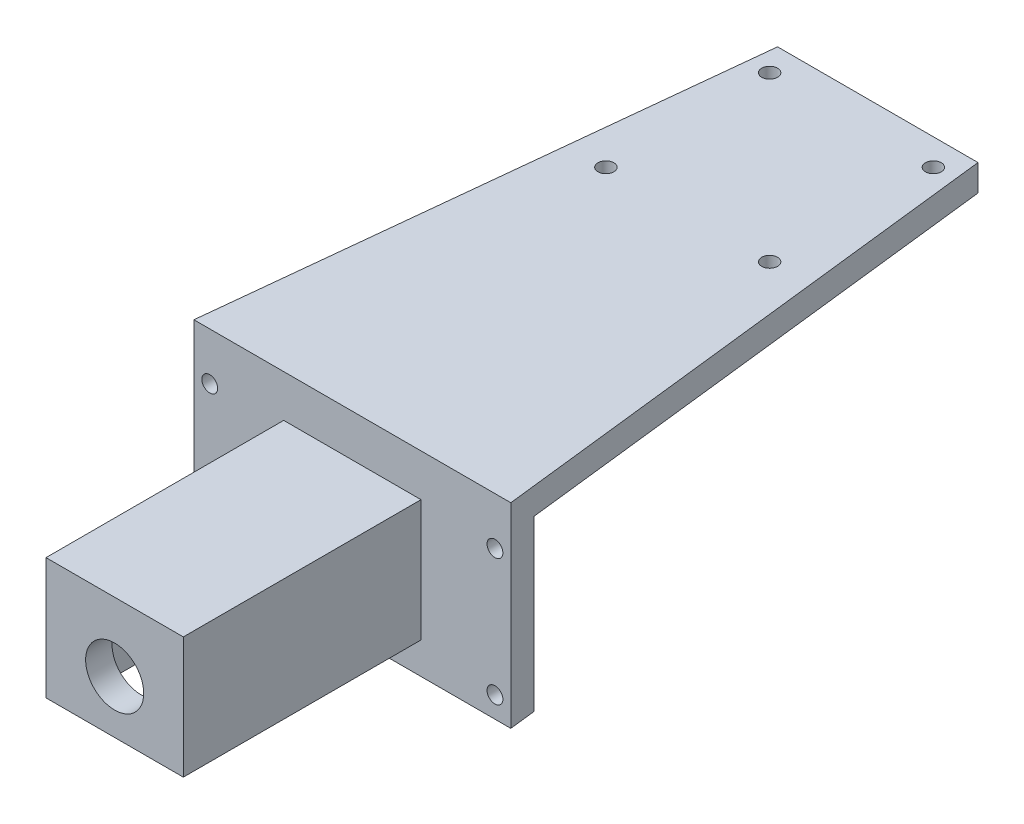
SolidWorks part; units mm, degrees
ref_plane "Front Plane" through (0, 0, 0) normal (0, 0, 1) x (1, 0, 0)
ref_plane "Top Plane" through (0, 0, 0) normal (0, 1, 0) x (1, 0, 0)
ref_plane "Right Plane" through (0, 0, 0) normal (1, 0, 0) x (0, 0, -1)
sketch "Sketch1" plane through (0, 0, 0) normal (0, 0, 1) x (1, 0, 0)
  line L1 (30, -16) -> (-30, -16)
  line L2 (30, -16) -> (30, 16)
  line L3 (30, 16) -> (-30, 16)
  line L4 (-30, -16) -> (-30, 16)
  line L5 (30, -16) -> (-30, 16) construction
  line L6 (30, 16) -> (-30, -16) construction
  point P0 (0, 0)
  dimension "D1" = 32
  dimension "D2" = 60
extrude "Boss-Extrude1" add sketch "Sketch1" along normal blind 5
sketch "Sketch2" plane through (0, 0, 5) normal (0, 0, 1) x (1, 0, 0)
  line L0 (30, 16) -> (-30, 16) construction
  line L1 (-30, -16) -> (30, -16) construction
  line L2 (30, -16) -> (30, 16) construction
  line L3 (-30, 16) -> (-30, -16) construction
  circle A0 centre (27, 12) radius 1.5
  circle A1 centre (27, -12) radius 1.5
  circle A2 centre (-27, -12) radius 1.5
  circle A3 centre (-27, 12) radius 1.5
  dimension "D9" = 3
  dimension "D10" = 3
  dimension "D11" = 3
  dimension "D12" = 3
  dimension "D1" = 4
  dimension "D2" = 4
  dimension "D3" = 4
  dimension "D4" = 4
  dimension "D5" = 3
  dimension "D6" = 3
  dimension "D7" = 3
  dimension "D8" = 3
extrude "Cut-Extrude1" cut sketch "Sketch2" against normal blind 5
sketch "Sketch3" plane through (0, 0, 5) normal (0, 0, 1) x (1, 0, 0)
  line L0 (-30, 16) -> (30, -16) construction
  line L1 (30, -16) -> (30, 16) construction
  line L2 (30, 16) -> (-30, -16) construction
sketch "Sketch4" plane through (0, 0, 5) normal (0, 0, 1) x (1, 0, 0)
  circle A0 centre (0, 0) radius 5
  dimension "D1" = 10
extrude "Cut-Extrude2" cut sketch "Sketch4" against normal blind 5
sketch "Sketch5" plane through (0, 0, 5) normal (0, 0, 1) x (1, 0, 0)
  line L1 (-30, 16) -> (30, 16)
  line L2 (-30, 16) -> (-30, 21)
  line L3 (-30, 21) -> (30, 21)
  line L4 (30, 16) -> (30, 21)
  dimension "D1" = 5
extrude "Boss-Extrude2" add sketch "Sketch5" against normal blind 100
sketch "Sketch6" plane through (0, 16, 0) normal (0, -1, 0) x (1, 0, 0)
  line L0 (30, -95) -> (30, 0) construction
  line L1 (-16, -90) -> (15, -90)
  line L2 (-16, -90) -> (-16, -59)
  line L3 (-16, -59) -> (15, -59)
  line L4 (15, -90) -> (15, -59)
  line L7 (-30, -95) -> (30, -95) construction
  circle A0 centre (15, -59) radius 1.5
  circle A1 centre (-16, -59) radius 1.5
  circle A2 centre (15, -90) radius 1.5
  circle A3 centre (-16, -90) radius 1.5
  dimension "D5" = 3
  dimension "D6" = 3
  dimension "D7" = 3
  dimension "D8" = 3
  dimension "D1" = 31
  dimension "D2" = 31
  dimension "D3" = 15
  dimension "D4" = 5
extrude "Cut-Extrude3" cut sketch "Sketch6" against normal blind 100 contours A0 | A1 | A2 | A3
sketch "Sketch7" plane through (0, 21, 0) normal (0, 1, 0) x (1, 0, 0)
  line L0 (30, -5) -> (18.449, 95)
  line L1 (30, 95) -> (-30, 95) construction
  line L2 (-30, -5) -> (-19.4968, 95)
  line L3 (-19.4968, 95) -> (-30, 95)
  line L4 (-30, 95) -> (-30, -5)
  line L5 (18.449, 95) -> (30, 95)
  line L6 (30, 95) -> (30, -5)
  point P7 (15, 90)
  point P8 (-16, 90)
  dimension "D1" = 4
  dimension "D2" = 4
extrude "Cut-Extrude4" cut sketch "Sketch7" against normal blind 100
sketch "Sketch8" plane through (0, 0, 5) normal (0, 0, 1) x (1, 0, 0)
  line L0 (13, 13) -> (-13, 13)
  line L2 (10, -10) -> (10, 10)
  line L3 (10, 10) -> (-10, 10)
  line L4 (-10, -10) -> (-10, 10)
  line L5 (10, -10) -> (-10, 10) construction
  line L6 (10, 10) -> (-10, -10) construction
  line L7 (-13, -10) -> (-13, 13)
  line L9 (13, -10) -> (13, 13)
  line L10 (13, -13) -> (-13, -13) construction
  line L11 (10, -10) -> (-10, -10) construction
  line L12 (13, -10) -> (10, -10)
  line L13 (13, -13) -> (13, 13) construction
  line L14 (-13, -13) -> (-13, 13) construction
  line L15 (-10, -10) -> (-13, -10)
  point P0 (0, 0)
  dimension "D2" = 20
  dimension "D3" = 3
extrude "Boss-Extrude3" add sketch "Sketch8" along normal blind 45
sketch "Sketch9" plane through (0, 0, 50) normal (0, 0, 1) x (1, 0, 0)
  line L0 (-13, -10) -> (13, -10)
  line L2 (-13, -10) -> (-13, 13)
  line L3 (-13, 13) -> (13, 13)
  line L4 (13, -10) -> (13, 13)
  line L5 (-10, -10) -> (13, 13) construction
  line L6 (-13, 13) -> (10, -10) construction
  point P0 (0, 0)
extrude "Boss-Extrude4" add sketch "Sketch9" against normal blind 5
sketch "Sketch10" plane through (0, 0, 50) normal (0, 0, 1) x (1, 0, 0)
  circle A0 centre (0, 0) radius 5.5
  dimension "D1" = 11
extrude "Cut-Extrude5" cut sketch "Sketch10" against normal blind 5
